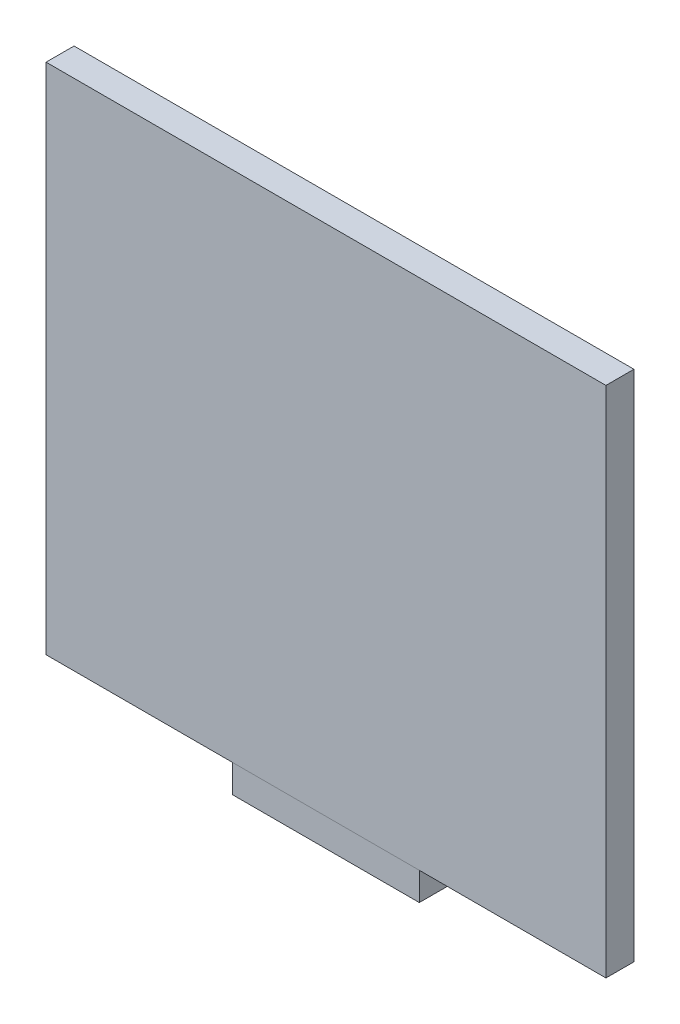
SolidWorks part; units mm, degrees
material "Acrylic (Medium-high impact)"
ref_plane "Front Plane" through (0, 0, 0) normal (0, 0, 1) x (1, 0, 0)
ref_plane "Top Plane" through (0, 0, 0) normal (0, 1, 0) x (1, 0, 0)
ref_plane "Right Plane" through (0, 0, 0) normal (1, 0, 0) x (0, 0, -1)
sketch "Sketch2" plane through (0, 0, 0) normal (0, 0, 1) x (1, 0, 0)
  line L1 (0, 0) -> (60, 0)
  line L2 (0, 0) -> (0, 55)
  line L3 (0, 55) -> (60, 55)
  line L4 (60, 0) -> (60, 55)
  dimension "D1" = 60
  dimension "D2" = 55
extrude "Boss-Extrude1" add sketch "Sketch2" against normal blind 3
sketch "Sketch3" plane through (0, 0, 0) normal (0, 0, 1) x (1, 0, 0)
  line L0 (0, 0) -> (60, 0) construction
  line L1 (20, 0) -> (40, 0)
  line L2 (20, 0) -> (20, -3)
  line L3 (20, -3) -> (40, -3)
  line L4 (40, 0) -> (40, -3)
  dimension "D1" = 3
  dimension "D2" = 20
  dimension "D3" = 20
extrude "Boss-Extrude2" add sketch "Sketch3" against normal blind 3 separate body
